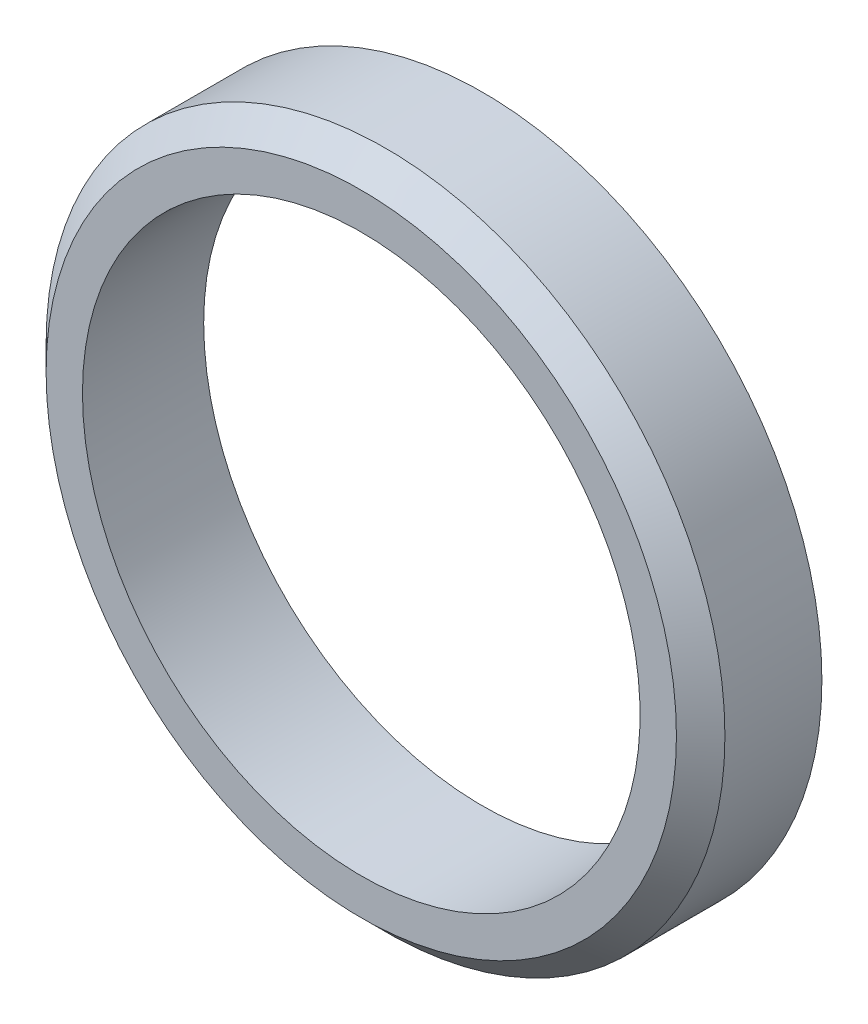
SolidWorks part; units mm, degrees
ref_plane "Спереди" through (0, 0, 0) normal (0, 0, 1) x (1, 0, 0)
ref_plane "Сверху" through (0, 0, 0) normal (0, 1, 0) x (1, 0, 0)
ref_plane "Справа" through (0, 0, 0) normal (1, 0, 0) x (0, 0, -1)
sketch "Эскиз1" plane through (0, 0, 0) normal (0, 0, 1) x (1, 0, 0)
  circle A0 centre (0, 0) radius 70
  dimension "D1" = 140
extrude "Бобышка-Вытянуть1" add sketch "Эскиз1" along normal blind 25
chamfer "Фаска1" distance 5 angle 45 1 edges at (70, 0, 25)
sketch "Эскиз2" plane through (0, 0, 0) normal (0, 0, -1) x (-1, 0, 0)
  circle A0 centre (0, 0) radius 57.5
  dimension "D1" = 115
extrude "Вырез-Вытянуть1" cut sketch "Эскиз2" against normal through all
